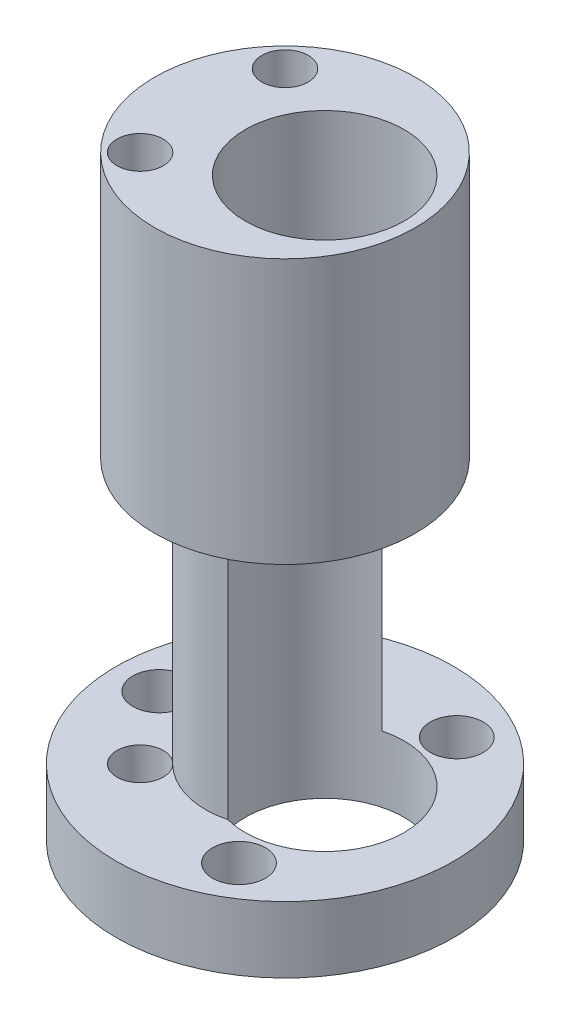
SolidWorks part; units mm, degrees
material "Brass"
ref_plane "Front Plane" through (0, 0, 0) normal (0, 0, 1) x (1, 0, 0)
ref_plane "Top Plane" through (0, 0, 0) normal (0, 1, 0) x (1, 0, 0)
ref_plane "Right Plane" through (0, 0, 0) normal (1, 0, 0) x (0, 0, -1)
sketch "Sketch1" plane through (0, 0, 0) normal (0, 1, 0) x (1, 0, 0)
  line L0 (0, 0) -> (0, 22.4741) construction
  line L1 (0, 0) -> (24.5888, 0) construction
  line L2 (0, 0) -> (11.7568, 15.5204) construction
  line L3 (0, 0) -> (17.1333, -14.1583) construction
  circle A0 centre (0, 0) radius 12.75
  dimension "D1" = 25.5
extrude "Boss-Extrude1" add sketch "Sketch1" along normal blind 5
sketch "Sketch2" plane through (0, 5, 0) normal (0, 1, 0) x (1, 0, 0)
  line L0 (0, 0) -> (-22.0865, 0) construction
  line L1 (0, 0) -> (7.5371, 13.0546) construction
  line L2 (0, 0) -> (6.8003, -11.7784) construction
  circle A0 centre (0, 0) radius 6
  circle A1 centre (0, 0) radius 9.5 construction
  point P6 (-9.5, 0)
  point P8 (4.75, 8.2272)
  point P9 (4.75, -8.2272)
  dimension "D1" = 12
  dimension "D2" = 19
  dimension "D3" = 120
  dimension "D4" = 120
hole_wizard "Ø6.0mm Dowel Hole1" positions "Sketch4" profile "Sketch3" hole size "Ø6.0" standard "ANSI Metric" end condition up to next
sketch "Sketch4" plane through (0, 5, 0) normal (0, 1, 0) x (1, 0, 0)
  point P0 (-9.5, 0)
  point P3 (4.75, -8.2272)
  point P6 (4.75, 8.2272)
sketch "Sketch3" plane through (-9.5, 5, 0) normal (1, 0, 0) x (0, 0, 1)
  line L0 (0, 0) -> (0, 5)
  line L1 (0, 5) -> (2, 5)
  line L2 (2, 5) -> (2, 0)
  line L5 (2, 0) -> (0, 0)
  line L11 (0, -6.35) -> (0, 107.95) construction
  dimension "Thru Hole Dia." = 4
  dimension "Thru Hole Depth" = 5
extrude "Boss-Extrude2" add sketch "Sketch2" along normal blind 20 contours A0
sketch "Sketch5" plane through (0, 25, 0) normal (0, 1, 0) x (1, 0, 0)
  circle A0 centre (0, 0) radius 9.85
  dimension "D1" = 19.7
extrude "Boss-Extrude3" add sketch "Sketch5" along normal blind 20
sketch "Sketch6" plane through (0, 45, 0) normal (0, 1, 0) x (1, 0, 0)
  line L0 (0, 0) -> (18.4476, 0) construction
  line L1 (0, 0) -> (-18.5099, 0) construction
  line L2 (0, 0) -> (8.7473, 15.1508) construction
  line L3 (0, 0) -> (7.5767, -13.1232) construction
  circle A0 centre (0, 0) radius 9.85 construction
  point P2 (3, 0)
  point P8 (4.925, 8.5304)
  point P9 (4.925, -8.5304)
  point P10 (-9.85, 0)
  dimension "D4" = 19.7
  dimension "D1" = 3
  dimension "D2" = 120
  dimension "D3" = 120
hole_wizard "Ø6.0mm Dowel Hole2" positions "Sketch8" profile "Sketch7" hole size "Ø6.0" standard "ANSI Metric"
sketch "Sketch8" plane through (0, 45, 0) normal (0, 1, 0) x (1, 0, 0)
  point P0 (3, 0)
sketch "Sketch7" plane through (3, 45, 0) normal (1, 0, 0) x (0, 0, 1)
  line L0 (0, 0) -> (0, 44.999)
  line L1 (0, 44.999) -> (6, 44.999)
  line L2 (6, 44.999) -> (6, 0)
  line L5 (6, 0) -> (0, 0)
  line L10 (0, 44.999) -> (-6, 44.999) construction
  line L11 (0, -6.35) -> (0, 107.95) construction
  dimension "Hole Dia." = 12
  dimension "Hole Depth" = 44.999
  dimension "Drill Angle" = 180
ref_plane "Plane1" through (4.925, 45, -8.5304) normal (0.5, 0, -0.866) x (-0.866, 0, -0.5)
sketch "Sketch9" plane through (4.925, 45, -8.5304) normal (0.5, 0, -0.866) x (-0.866, 0, -0.5)
  point P0 (0, -10)
  dimension "D1" = 10
ref_plane "Plane2" through (4.925, 45, 8.5304) normal (0.5, 0, 0.866) x (0.866, 0, -0.5)
sketch "Sketch10" plane through (4.925, 45, 8.5304) normal (0.5, 0, 0.866) x (0.866, 0, -0.5)
  point P0 (0, -10)
  dimension "D1" = 10
ref_plane "Plane3" through (-9.85, 45, 0) normal (-1, 0, 0) x (0, 0, 1)
sketch "Sketch12" plane through (-9.85, 45, 0) normal (-1, 0, 0) x (0, 0, 1)
  point P0 (0, -10)
  dimension "D1" = 10
sketch "Sketch13" plane through (0, 45, 0) normal (0, 1, 0) x (1, 0, 0)
  line L0 (0, 0) -> (-15.1252, 15.1252) construction
  line L1 (0, 0) -> (-18.5099, 0) construction
  line L2 (0, 0) -> (-15.3988, -15.3988) construction
  circle A0 centre (0, 0) radius 7.74 construction
  point P7 (-5.473, 5.473)
  point P8 (-5.473, -5.473)
  dimension "D3" = 15.48
  dimension "D1" = 45
  dimension "D2" = 45
hole_wizard "Ø6.0mm Dowel Hole3" positions "Sketch15" profile "Sketch16" hole size "Ø6.0" standard "ANSI Metric"
sketch "Sketch15" plane through (0, 45, 0) normal (0, 1, 0) x (1, 0, 0)
  point P0 (-5.473, 5.473)
  point P3 (-5.473, -5.473)
sketch "Sketch16" plane through (-5.473, 45, -5.473) normal (1, 0, 0) x (0, 0, 1)
  line L0 (0, 0) -> (0, 20)
  line L1 (0, 20) -> (1.75, 20)
  line L2 (1.75, 20) -> (1.75, 0)
  line L5 (1.75, 0) -> (0, 0)
  line L11 (0, -6.35) -> (0, 107.95) construction
  dimension "Thru Hole Dia." = 3.5
  dimension "Thru Hole Depth" = 20
hole_wizard "Ø6.0mm Dowel Hole4" positions "Sketch18" profile "Sketch17" hole size "Ø6.0" standard "ANSI Metric"
sketch "Sketch18" plane through (0, 5, 0) normal (0, 1, 0) x (1, 0, 0)
  point P0 (-5.473, -5.473)
  point P3 (-5.473, 5.473)
sketch "Sketch17" plane through (-5.473, 5, 5.473) normal (1, 0, 0) x (0, 0, 1)
  line L0 (0, 0) -> (0, 5)
  line L1 (0, 5) -> (1.75, 5)
  line L2 (1.75, 5) -> (1.75, 0)
  line L5 (1.75, 0) -> (0, 0)
  line L11 (0, -6.35) -> (0, 107.95) construction
  dimension "Thru Hole Dia." = 3.5
  dimension "Thru Hole Depth" = 5
